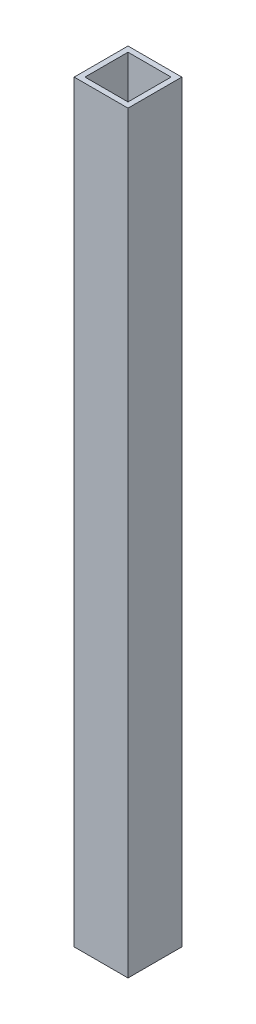
SolidWorks part; units mm, degrees
material "AISI 1015 Steel, Cold Drawn (SS)"
ref_plane "Front Plane" through (0, 0, 0) normal (0, 0, 1) x (1, 0, 0)
ref_plane "Top Plane" through (0, 0, 0) normal (0, 1, 0) x (1, 0, 0)
ref_plane "Right Plane" through (0, 0, 0) normal (1, 0, 0) x (0, 0, -1)
sketch "Sketch1" plane through (0, 0, 0) normal (0, 1, 0) x (1, 0, 0)
  line L0 (5, 5) -> (5, 45)
  line L1 (0, 0) -> (50, 0)
  line L2 (0, 0) -> (0, 50)
  line L3 (0, 50) -> (50, 50)
  line L4 (50, 0) -> (50, 50)
  line L5 (5, 45) -> (45, 45)
  line L6 (45, 5) -> (45, 45)
  line L7 (5, 5) -> (45, 5)
  dimension "D1" = 50
  dimension "D2" = 50
  dimension "D3" = 5
extrude "Boss-Extrude1" add sketch "Sketch1" along normal blind 700
